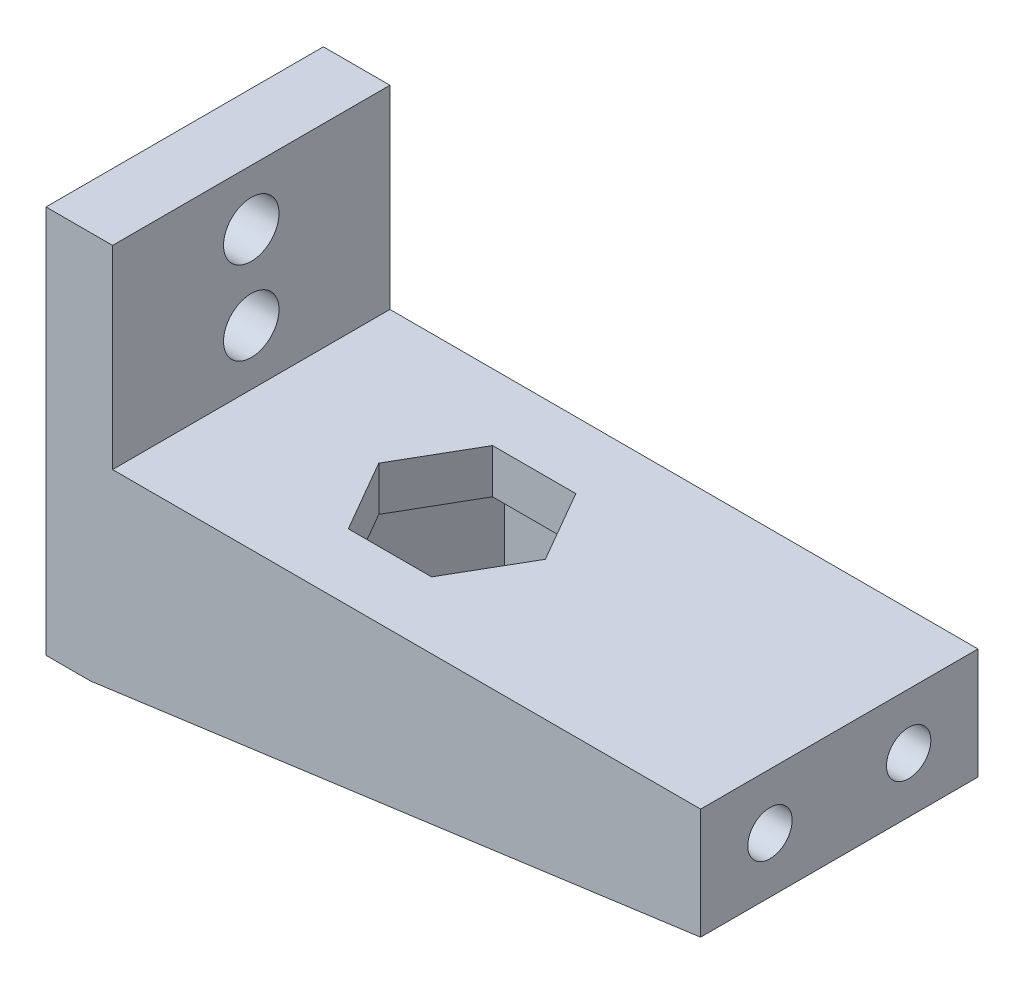
SolidWorks part; units mm, degrees
ref_plane "Alzado" through (0, 0, 0) normal (0, 0, 1) x (1, 0, 0)
ref_plane "Planta" through (0, 0, 0) normal (0, 1, 0) x (1, 0, 0)
ref_plane "Vista lateral" through (0, 0, 0) normal (1, 0, 0) x (0, 0, -1)
sketch "Croquis3" plane through (0, 0, 0) normal (1, 0, 0) x (0, 0, -1)
  line L1 (-8.1731, 20.3125) -> (16.8269, 20.3125)
  line L2 (-8.1731, 20.3125) -> (-8.1731, -14.6875)
  line L3 (-8.1731, -14.6875) -> (16.8269, -14.6875)
  line L4 (16.8269, 20.3125) -> (16.8269, -14.6875)
  dimension "D1" = 25
  dimension "D2" = 35
extrude "Saliente-Extruir2" add sketch "Croquis3" along normal blind 4
sketch "Croquis5" plane through (4, 0, 0) normal (1, 0, 0) x (0, 0, -1)
  line L0 (16.8269, -14.6875) -> (16.8269, 20.3125) construction
  line L1 (-8.1731, 20.3125) -> (16.8269, 20.3125)
  line L2 (-8.1731, 20.3125) -> (-8.1731, 2.8125)
  line L3 (-8.1731, 2.8125) -> (16.8269, 2.8125)
  line L4 (16.8269, 20.3125) -> (16.8269, 2.8125)
extrude "Saliente-Extruir3" add sketch "Croquis5" along normal blind 2
sketch "Croquis7" plane through (4, 0, 0) normal (1, 0, 0) x (0, 0, -1)
  line L0 (16.8269, -14.6875) -> (16.8269, 2.8125) construction
  line L1 (-8.1731, 2.8125) -> (16.8269, 2.8125)
  line L2 (-8.1731, 2.8125) -> (-8.1731, -7.1875)
  line L3 (-8.1731, -7.1875) -> (16.8269, -7.1875)
  line L4 (16.8269, 2.8125) -> (16.8269, -7.1875)
  dimension "D1" = 10
extrude "Saliente-Extruir5" add sketch "Croquis7" along normal blind 55
sketch "Croquis8" plane through (6, 0, 0) normal (1, 0, 0) x (0, 0, -1)
  line L0 (16.8269, 20.3125) -> (-8.1731, 20.3125) construction
  circle A0 centre (4.3269, 15.3125) radius 2.5
  circle A1 centre (4.3269, 7.8125) radius 2.5
  dimension "D1" = 5
  dimension "D2" = 5
  dimension "D3" = 7.5
  dimension "D4" = 5
extrude "Cortar-Extruir1" cut sketch "Croquis8" against normal blind 55
sketch "Croquis9" plane through (0, 2.8125, 0) normal (0, 1, 0) x (1, 0, 0)
  line L0 (59, 16.8269) -> (6, 16.8269) construction
  line L1 (32.5056, 4.3269) -> (28.7528, 10.8269)
  line L2 (28.7528, 10.8269) -> (21.2472, 10.8269)
  line L3 (21.2472, 10.8269) -> (17.4944, 4.3269)
  line L4 (17.4944, 4.3269) -> (21.2472, -2.1731)
  line L5 (21.2472, -2.1731) -> (28.7528, -2.1731)
  line L6 (28.7528, -2.1731) -> (32.5056, 4.3269)
  line L9 (0, 16.8269) -> (0, -8.1731) construction
  circle A0 centre (25, 4.3269) radius 6.5 construction
  dimension "D1" = 13
  dimension "D2" = 25
sketch "Croquis10" plane through (0, 0, 8.1731) normal (0, 0, 1) x (1, 0, 0)
  line L0 (4, -14.6875) -> (59, -7.1875)
  line L1 (59, -7.1875) -> (4, -7.1875)
  line L2 (4, -7.1875) -> (4, -14.6875)
extrude "Saliente-Extruir6" add sketch "Croquis10" against normal through all
extrude "Cortar-Extruir3" cut sketch "Croquis9" against normal blind 4
sketch "Croquis11" plane through (59, 0, 0) normal (1, 0, 0) x (0, 0, -1)
  line L2 (16.8269, -7.1875) -> (16.8269, 2.8125) construction
  line L6 (-8.1731, 2.8125) -> (16.8269, 2.8125) construction
  circle A0 centre (-1.9231, -2.1875) radius 2
  circle A1 centre (10.5769, -2.1875) radius 2
  dimension "D1" = 4
  dimension "D2" = 4
  dimension "D3" = 12.5
  dimension "D4" = 6.25
  dimension "D5" = 5
extrude "Cortar-Extruir4" cut sketch "Croquis11" against normal blind 20
sketch "Croquis12" plane through (0, -1.1875, 0) normal (0, 1, 0) x (1, 0, 0)
  line L0 (28.7528, 10.8269) -> (21.2472, 10.8269) construction
  line L1 (30.2539, 13.4269) -> (19.7461, 13.4269)
  line L2 (19.7461, 13.4269) -> (14.4922, 4.3269)
  line L3 (14.4922, 4.3269) -> (19.7461, -4.7731)
  line L4 (19.7461, -4.7731) -> (30.2539, -4.7731)
  line L5 (30.2539, -4.7731) -> (35.5078, 4.3269)
  line L6 (35.5078, 4.3269) -> (30.2539, 13.4269)
  line L7 (0, 16.8269) -> (0, -8.1731) construction
  circle A0 centre (25, 4.3269) radius 9.1 construction
  dimension "D1" = 18.2
  dimension "D2" = 25
extrude "Cortar-Extruir5" cut sketch "Croquis12" against normal blind 45
